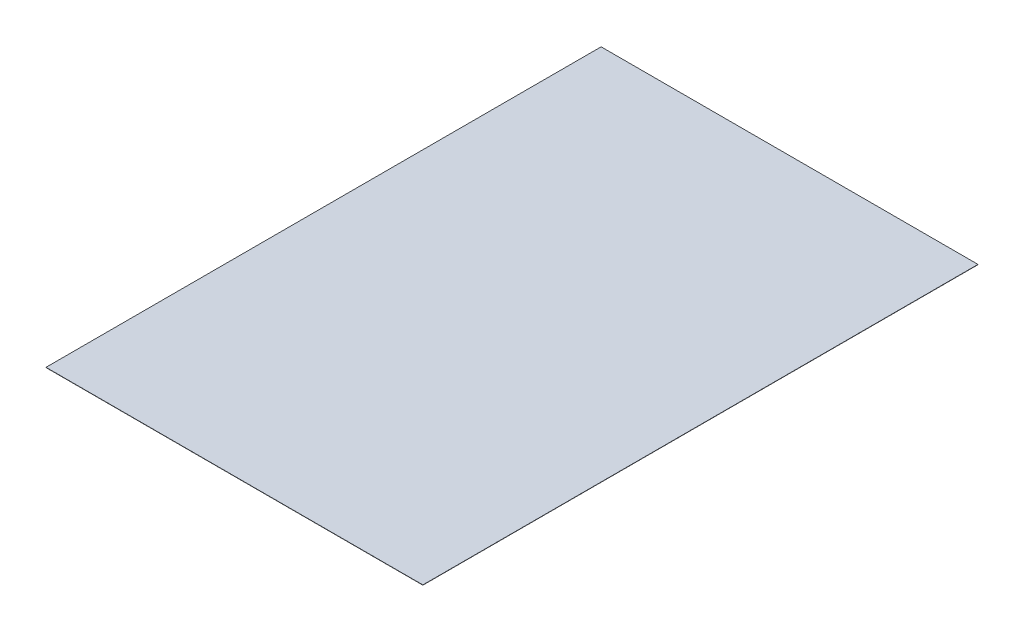
SolidWorks part; units mm, degrees
ref_plane "Front Plane" through (0, 0, 0) normal (0, 0, 1) x (1, 0, 0)
ref_plane "Top Plane" through (0, 0, 0) normal (0, 1, 0) x (1, 0, 0)
ref_plane "Right Plane" through (0, 0, 0) normal (1, 0, 0) x (0, 0, -1)
sketch "Sketch1" plane through (0, 0, 0) normal (0, 1, 0) x (1, 0, 0)
  line L1 (3700, -5450) -> (-3700, -5450)
  line L2 (3700, -5450) -> (3700, 5450)
  line L3 (3700, 5450) -> (-3700, 5450)
  line L4 (-3700, -5450) -> (-3700, 5450)
  line L5 (3700, -5450) -> (-3700, 5450) construction
  line L6 (3700, 5450) -> (-3700, -5450) construction
  point P0 (0, 0)
  dimension "D1" = 7400
  dimension "D2" = 10900
extrude "Boss-Extrude1" add sketch "Sketch1" along normal blind 5
